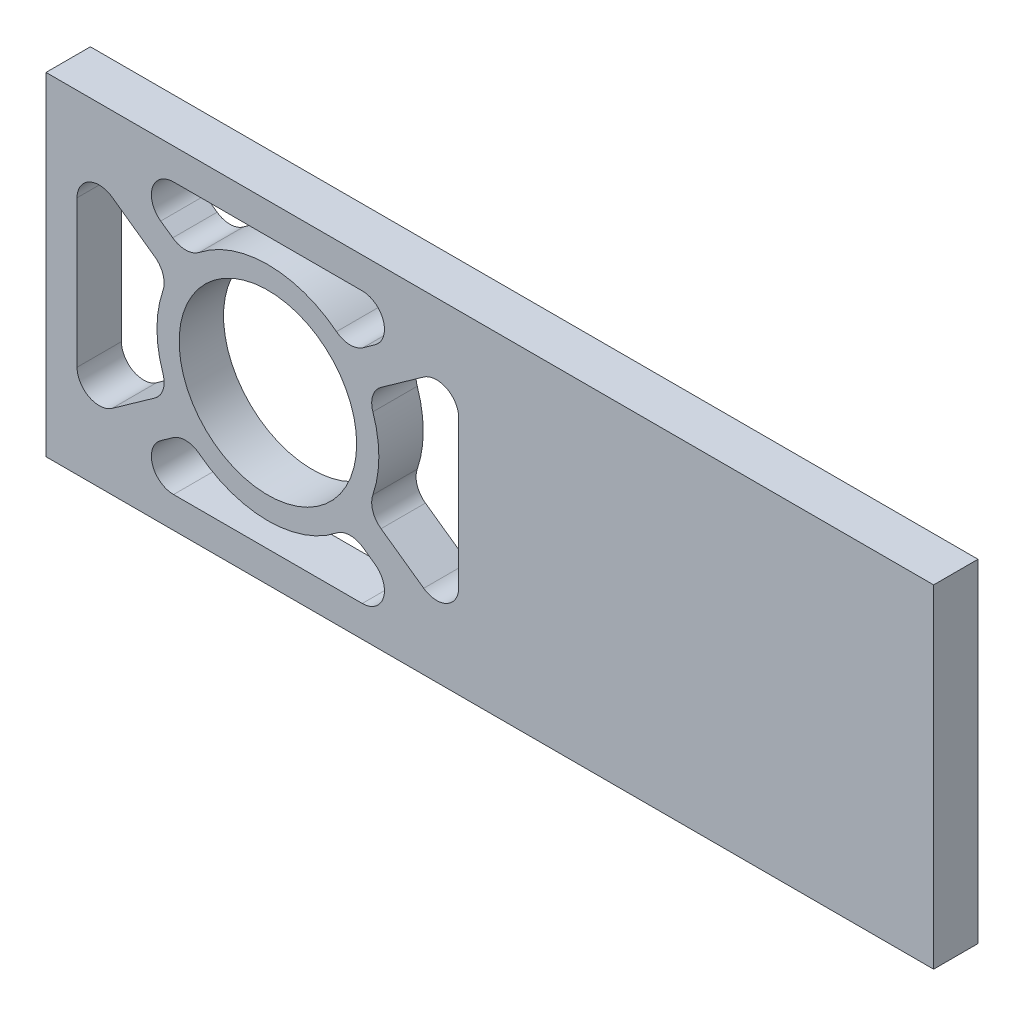
SolidWorks part; units mm, degrees
ref_plane "Front" through (0, 0, 0) normal (0, 0, 1) x (1, 0, 0)
ref_plane "Top" through (0, 0, 0) normal (0, 1, 0) x (1, 0, 0)
ref_plane "Right" through (0, 0, 0) normal (1, 0, 0) x (0, 0, -1)
sketch "Sketch1" plane through (0, 0, 0) normal (0, 0, 1) x (1, 0, 0)
  line L0 (-50, 37.5) -> (-50, -37.5)
  line L1 (-50, -37.5) -> (150, -37.5)
  line L2 (150, -37.5) -> (150, 37.5)
  line L3 (150, 37.5) -> (-50, 37.5)
  line L5 (-37.5, -37.5) -> (37.5, 37.5) construction
  line L12 (-37.5, 37.5) -> (37.5, -37.5) construction
  point P5 (0, 0)
  dimension "D1" = 75
  dimension "D2" = 50
  dimension "D3" = 200
extrude "Boss-Extrude3" add sketch "Sketch1" along normal mid plane 10
sketch "Sketch2" plane through (0, 0, 5) normal (0, 0, 1) x (1, 0, 0)
  circle A0 centre (0, 0) radius 20
  dimension "D1" = 40
extrude "Cut-Extrude1" cut sketch "Sketch2" against normal through all
sketch "Sketch3" plane through (0, 0, 5) normal (0, 0, 1) x (1, 0, 0)
  line L0 (-43, 26.209) -> (-43, -26.209)
  line L1 (-43, -26.209) -> (-22.2154, -11.4664)
  line L2 (-43, 26.209) -> (-22.2154, 11.4664)
  line L3 (-36.9503, 30.5) -> (36.9503, 30.5)
  line L4 (36.9503, 30.5) -> (18.1656, 17.1759)
  line L5 (-36.9503, 30.5) -> (-18.1656, 17.1759)
  line L6 (22.2154, 11.4664) -> (43, 26.209)
  line L7 (43, 26.209) -> (43, -26.209)
  line L8 (43, -26.209) -> (22.2154, -11.4664)
  line L9 (0, 30.5) -> (0, -30.5) construction
  line L10 (-43, 0) -> (43, 0) construction
  line L11 (150, 37.5) -> (-50, 37.5) construction
  line L12 (-18.1656, -17.1759) -> (-36.9503, -30.5)
  line L13 (-36.9503, -30.5) -> (36.9503, -30.5)
  line L14 (36.9503, -30.5) -> (18.1656, -17.1759)
  line L15 (-50, -37.5) -> (150, -37.5) construction
  line L16 (-50, 37.5) -> (-50, -37.5) construction
  line L17 (150, -37.5) -> (150, 37.5) construction
  line L18 (-43, 30.5) -> (43, -30.5) construction
  circle A0 centre (0, 0) radius 25 construction
  circle A2 centre (0, 0) radius 20 construction
  arc A3 (-18.1656, 17.1759) -> (18.1656, 17.1759) centre (0, 0) cw
  arc A4 (22.2154, 11.4664) -> (22.2154, -11.4664) centre (0, 0) cw
  arc A5 (18.1656, -17.1759) -> (-18.1656, -17.1759) centre (0, 0) cw
  arc A6 (-22.2154, -11.4664) -> (-22.2154, 11.4664) centre (0, 0) cw
  point P20 (0, 0)
  dimension "D4" = 5
  dimension "D1" = 7
  dimension "D2" = 7
  dimension "D3" = 7
extrude "Cut-Extrude2" cut sketch "Sketch3" against normal through all
fillet "Fillet1" radius 5 16 edges at (-36.9503, -30.5, 0) (-18.1656, -17.1759, 0) (18.1656, -17.1759, 0) (36.9503, -30.5, 0) (-43, -26.209, 0) (-43, 26.209, 0) (-22.2154, -11.4664, 0) (-22.2154, 11.4664, 0) (-36.9503, 30.5, 0) (36.9503, 30.5, 0) (-18.1656, 17.1759, 0) (18.1656, 17.1759, 0) (43, -26.209, 0) (43, 26.209, 0) (22.2154, 11.4664, 0) (22.2154, -11.4664, 0)
